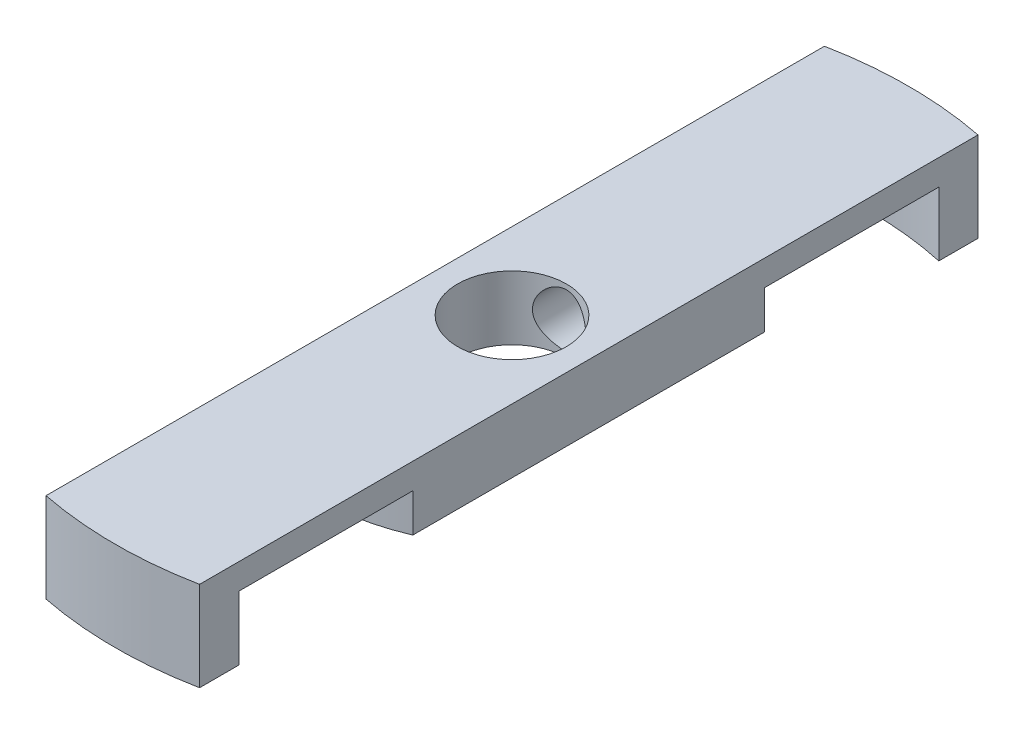
SolidWorks part; units mm, degrees
ref_plane "Plano frontal" through (0, 0, 0) normal (0, 0, 1) x (1, 0, 0)
ref_plane "Plano superior" through (0, 0, 0) normal (0, 1, 0) x (1, 0, 0)
ref_plane "Plano direito" through (0, 0, 0) normal (1, 0, 0) x (0, 0, -1)
sketch "Esboço1" plane through (0, 0, 0) normal (0, 0, 1) x (1, 0, 0)
  line L0 (0, 0) -> (0, 5.1163) construction
  line L1 (4.25, 5) -> (4.25, 0)
  line L9 (15, 0) -> (15, 3)
  line L10 (4.25, 5) -> (31, 5)
  line L11 (31, 5) -> (31, -2)
  line L12 (31, -2) -> (28, -2)
  line L13 (28, -2) -> (28, 3)
  line L14 (28, 3) -> (15, 3)
  line L15 (15, 0) -> (4.25, 0)
  point P5 (9.5213, 4)
  point P6 (5.245, 4)
  dimension "D3" = 2
  dimension "D1" = 8.5
  dimension "D2" = 30
  dimension "D4" = 5
  dimension "D7" = 2
  dimension "D9" = 3
  dimension "D10" = 62
revolve "Revolução1" add sketch "Esboço1" angle 360 about L0
sketch "Esboço2" plane through (0, 5, 0) normal (0, 1, 0) x (1, 0, 0)
  line L1 (-6, 38.1351) -> (6, 38.1351)
  line L2 (-6, 38.1351) -> (-6, -38.1351)
  line L3 (-6, -38.1351) -> (6, -38.1351)
  line L4 (6, 38.1351) -> (6, -38.1351)
  line L5 (-6, 38.1351) -> (6, -38.1351) construction
  line L6 (-6, -38.1351) -> (6, 38.1351) construction
  line L7 (-48.3706, -51.1789) -> (48.3706, -51.1789)
  line L8 (-48.3706, -51.1789) -> (-48.3706, 51.1789)
  line L9 (-48.3706, 51.1789) -> (48.3706, 51.1789)
  line L10 (48.3706, -51.1789) -> (48.3706, 51.1789)
  line L11 (-48.3706, -51.1789) -> (48.3706, 51.1789) construction
  line L12 (-48.3706, 51.1789) -> (48.3706, -51.1789) construction
  point P0 (0, 0)
  point P6 (0, 0)
  dimension "D1" = 12
extrude "Corte-extrusão1" cut sketch "Esboço2" against normal through all both and the other way through all
sketch "Esboço3" plane through (0, 0, 0) normal (0, 0, 1) x (1, 0, 0)
  line L0 (0, 0) -> (0, 5) construction
  line L1 (4.25, 5) -> (-4.25, 5) construction
  circle A0 centre (0, 2.5) radius 2.1
  point P7 (0, 2)
  dimension "D1" = 4.2
extrude "Corte-extrusão4" cut sketch "Esboço3" against normal mid plane 26
